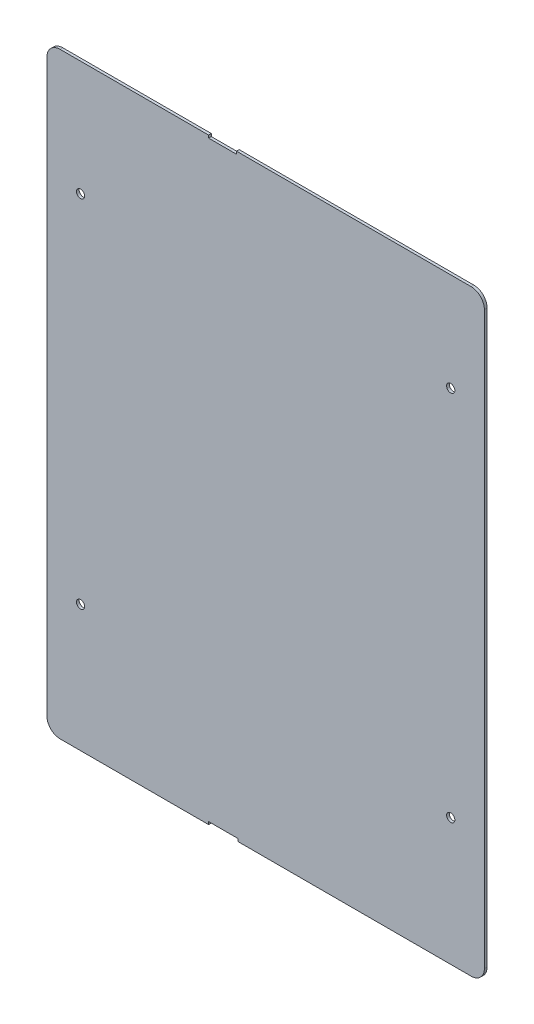
SolidWorks part; units mm, degrees
ref_plane "Front Plane" through (0, 0, 0) normal (0, 0, 1) x (1, 0, 0)
ref_plane "Top Plane" through (0, 0, 0) normal (0, 1, 0) x (1, 0, 0)
ref_plane "Right Plane" through (0, 0, 0) normal (1, 0, 0) x (0, 0, -1)
sketch "Sketch2" plane through (0, 0, 0) normal (0, 0, 1) x (1, 0, 0)
  line L0 (-43, 225.24) -> (-43, 223.24)
  line L1 (-165, 225.24) -> (-43, 225.24)
  line L2 (-165, 225.24) -> (-165, -225.24)
  line L3 (-165, -225.24) -> (-43, -225.24)
  line L4 (165, 225.24) -> (165, -225.24)
  line L5 (-165, 225.24) -> (165, -225.24) construction
  line L6 (-165, -225.24) -> (165, 225.24) construction
  line L7 (-43, 223.24) -> (-22, 223.24)
  line L8 (-22, 223.24) -> (-22, 225.24)
  line L9 (-22, 225.24) -> (165, 225.24)
  line L10 (-21, -225.24) -> (-21, -223.24)
  line L11 (-21, -223.24) -> (-43, -223.24)
  line L12 (-43, -223.24) -> (-43, -225.24)
  line L13 (-21, -225.24) -> (165, -225.24)
  point P0 (0, 0)
  dimension "D1" = 2
  dimension "Length 1" = 330
  dimension "D2" = 122
  dimension "Length 2" = 450.48
  dimension "D3" = 143
  dimension "D4" = 122
  dimension "D5" = 144
  dimension "D6" = 2
extrude "Boss-Extrude1" add sketch "Sketch2" along normal blind 2.032
sketch "Sketch3" [suppressed] plane through (0, 0, 2.032) normal (0, 0, 1) x (1, 0, 0)
  circle A0 centre (-175.117, 128.01) radius 3.1
  circle A1 centre (175.117, 128.01) radius 3.1
  circle A8 centre (-175.1171, -128.01) radius 3.1
  circle A9 centre (175.1169, -128.01) radius 3.1
  dimension "D1" = 6.2
extrude "Cut-Extrude1" [suppressed] cut sketch "Sketch3" against normal through all both and the other way through all
sketch "Sketch4" [suppressed] plane through (0, 0, 0) normal (0, 0, -1) x (-1, 0, 0)
  circle A0 centre (-423.777, 128.01) radius 3.1
  circle A1 centre (423.777, 128.01) radius 3.1
  circle A2 centre (423.777, -128.01) radius 3.1
  circle A3 centre (-423.777, -128.01) radius 3.1
  dimension "D1" = 6.2
extrude "Cut-Extrude2" [suppressed] cut sketch "Sketch4" against normal through all both and the other way through all
sketch "Sketch5" [suppressed] plane through (0, 0, 0) normal (0, 0, -1) x (-1, 0, 0)
  circle A0 centre (-175.117, -437.5) radius 3.1
  circle A1 centre (175.1169, -437.5) radius 3.1
  circle A2 centre (175.1169, 437.5) radius 3.1
  circle A3 centre (-175.117, 437.5) radius 3.1
  dimension "D1" = 6.2
extrude "Cut-Extrude3" [suppressed] cut sketch "Sketch5" against normal through all both and the other way through all
sketch "Sketch6" [suppressed] plane through (0, 0, 0) normal (0, 0, -1) x (-1, 0, 0)
  circle A0 centre (175.9, -175.117) radius 3.1
  circle A1 centre (175.9, 175.117) radius 3.1
  circle A2 centre (-175.9, 175.117) radius 3.1
  circle A3 centre (-175.9, -175.117) radius 3.1
  circle A5 centre (-175.9, 0) radius 3.1
  circle A6 centre (175.9, 0) radius 3.1
  dimension "D1" = 6.2
  dimension "D2" = 6.2
  dimension "D3" = 6.2
fillet "Fillet5" [suppressed] radius 10
extrude "Cut-Extrude4" [suppressed] cut sketch "Sketch6" against normal through all both and the other way through all
sketch "Sketch7" plane through (0, 0, 2.032) normal (0, 0, 1) x (1, 0, 0)
  circle A0 centre (-139.6, -129.6148) radius 3.1
  circle A1 centre (-139.6, 138.5552) radius 3.1
  circle A2 centre (139.6, 151.166) radius 3.1
  circle A3 centre (139.6, -129.36) radius 3.1
  dimension "D1" = 6.2
extrude "Cut-Extrude5" cut sketch "Sketch7" against normal through all both and the other way through all
fillet "Fillet4" radius 10 4 edges at (-165, -225.24, 1.016) (-165, 225.24, 1.016) (165, -225.24, 1.016) (165, 225.24, 1.016)
sketch "Sketch8" [suppressed] plane through (0, 0, 2.032) normal (0, 0, 1) x (1, 0, 0)
  line L0 (-37.3761, -47.01) -> (-37.3761, -22.01) construction
  line L1 (32.5, -51.886) -> (-32.5, -51.886) construction
  line L2 (37.376, -22.01) -> (37.376, -47.01) construction
  line L3 (-32.5, -17.1339) -> (32.5, -17.1339) construction
  line L4 (-37.3761, -47.01) -> (-37.3761, -22.01) construction
  line L5 (32.5, -51.886) -> (-32.5, -51.886) construction
  line L6 (37.376, -22.01) -> (37.376, -47.01) construction
  line L7 (-32.5, -17.1339) -> (32.5, -17.1339) construction
  line L8 (-37.6761, -47.01) -> (-37.6761, -22.01)
  line L9 (32.5, -52.186) -> (-32.5, -52.186)
  line L10 (37.676, -22.01) -> (37.676, -47.01)
  line L11 (-32.5, -16.8339) -> (32.5, -16.8339)
  arc A0 (-37.3761, -47.01) -> (-32.5, -51.886) centre (-32.5, -47.01) ccw construction
  arc A1 (32.5, -51.886) -> (37.376, -47.01) centre (32.5, -47.01) ccw construction
  arc A2 (37.376, -22.01) -> (32.5, -17.1339) centre (32.5, -22.01) ccw construction
  arc A3 (-32.5, -17.1339) -> (-37.3761, -22.01) centre (-32.5, -22.01) ccw construction
  arc A4 (-37.3761, -47.01) -> (-32.5, -51.886) centre (-32.5, -47.01) ccw construction
  arc A5 (32.5, -51.886) -> (37.376, -47.01) centre (32.5, -47.01) ccw construction
  arc A6 (37.376, -22.01) -> (32.5, -17.1339) centre (32.5, -22.01) ccw construction
  arc A7 (-32.5, -17.1339) -> (-37.3761, -22.01) centre (-32.5, -22.01) ccw construction
  arc A8 (-32.5, -16.8339) -> (-37.6761, -22.01) centre (-32.5, -22.01) ccw
  arc A9 (-37.6761, -47.01) -> (-32.5, -52.186) centre (-32.5, -47.01) ccw
  arc A10 (32.5, -52.186) -> (37.676, -47.01) centre (32.5, -47.01) ccw
  arc A11 (37.676, -22.01) -> (32.5, -16.8339) centre (32.5, -22.01) ccw
  dimension "D1" = 0.3
extrude "Cut-Extrude6" [suppressed] cut sketch "Sketch8" against normal through all
sketch "Sketch9" [suppressed] plane through (0, 0, 2.032) normal (0, 0, 1) x (1, 0, 0)
  line L0 (-51.9979, -76.9078) -> (-51.9979, -83.1078) construction
  line L1 (-48.8979, -76.9078) -> (-48.8979, -83.1078)
  line L2 (-55.0979, -76.9078) -> (-55.0979, -83.1078)
  line L3 (51.9978, -76.9078) -> (51.9978, -83.1078) construction
  line L4 (55.0978, -76.9078) -> (55.0978, -83.1078)
  line L5 (48.8978, -76.9078) -> (48.8978, -83.1078)
  circle A0 centre (-51.9979, -1.5121) radius 3.1
  circle A1 centre (51.9978, -1.5121) radius 3.1
  circle A2 centre (-51.9979, -80.0078) radius 3.1 construction
  arc A3 (-48.8979, -76.9078) -> (-55.0979, -76.9078) centre (-51.9979, -76.9078) ccw
  arc A4 (-55.0979, -83.1078) -> (-48.8979, -83.1078) centre (-51.9979, -83.1078) ccw
  circle A5 centre (51.9978, -80.0078) radius 3.1 construction
  arc A6 (55.0978, -76.9078) -> (48.8978, -76.9078) centre (51.9978, -76.9078) ccw
  arc A7 (48.8978, -83.1078) -> (55.0978, -83.1078) centre (51.9978, -83.1078) ccw
  point P11 (-51.9979, -80.0078)
  point P17 (51.9978, -80.0078)
  dimension "D1" = 6.2
extrude "Cut-Extrude7" [suppressed] cut sketch "Sketch9" against normal through all
sketch "Sketch10" [suppressed] plane through (0, 0, 2.032) normal (0, 0, 1) x (1, 0, 0)
  line L0 (90, 90.8143) -> (-90, 90.8143) construction
  line L1 (75.5, 121.0648) -> (-75.5, 121.0648) construction
  line L2 (75.5, 90.8143) -> (-75.5, 90.8143) construction
  line L3 (75.5, 121.0648) -> (-75.5, 121.0648) construction
  line L4 (75.5, 90.5143) -> (-75.5, 90.5143)
  line L5 (75.5, 121.3648) -> (-75.5, 121.3648)
  spline S0 degree 3 poles (7072.6895, 138.2935) (66.7513, 120.7508) (74.0721, 121.0685) (75.5298, 121.0647) (75.5326, 121.0647) (75.6464, 121.0643) (75.8632, 121.0597) (76.1642, 121.0437) (76.381, 121.0257) (76.5878, 121.0048) (76.7942, 120.9803) (77.0603, 120.9413) (77.3248, 120.8952) (77.5598, 120.8477) (77.7949, 120.7947) (77.9818, 120.7481) (78.1109, 120.7132) (78.2822, 120.6658) (78.5457, 120.5872) (78.9382, 120.4526) (79.2301, 120.3392) (79.3912, 120.2721) (79.5867, 120.1894) (79.8287, 120.0797) (80.0659, 119.9615) (80.3074, 119.8374) (80.4668, 119.7503) (80.8016, 119.5566) (81.1538, 119.3396) (81.5223, 119.0841) (81.7178, 118.9395) (81.8836, 118.8158) (82.0678, 118.6719) (82.2476, 118.5231) (82.4279, 118.3716) (82.5907, 118.2288) (82.7493, 118.0824) (82.9322, 117.9119) (83.2327, 117.6176) (83.6639, 117.1527) (83.9602, 116.8013) (84.1153, 116.6069) (84.2773, 116.4024) (84.4141, 116.2207) (84.6783, 115.8519) (84.9333, 115.4777) (85.2917, 114.8964) (85.6175, 114.311) (85.8168, 113.9147) (86.0153, 113.4997) (86.199, 113.0919) (86.3667, 112.6759) (86.5131, 112.2932) (86.6057, 112.0372) (86.6922, 111.7793) (86.7672, 111.5516) (86.8201, 111.3823) (86.9423, 110.9692) (87.0765, 110.4773) (87.247, 109.7286) (87.3625, 109.1005) (87.4598, 108.4609) (87.5282, 107.8937) (87.5661, 107.4468) (87.5939, 107.0493) (87.6148, 106.6536) (87.6234, 106.2582) (87.6251, 106.0243) (87.6252, 105.9711) (87.6249, 105.6521) (87.6131, 105.121) (87.5623, 104.3289) (87.4962, 103.7081) (87.4136, 103.0987) (87.3259, 102.565) (87.2377, 102.1278) (87.1497, 101.7237) (87.0462, 101.2874) (86.9261, 100.8539) (86.8399, 100.5642) (86.8173, 100.4902) (86.7193, 100.1763) (86.5601, 99.7025) (86.2936, 99.0104) (86.0691, 98.4959) (85.9353, 98.2118) (85.8046, 97.939) (85.5968, 97.5281) (85.2615, 96.9315) (84.9154, 96.3749) (84.674, 96.0215) (84.4707, 95.7372) (84.3836, 95.6191) (84.1969, 95.3742) (84.0085, 95.1357) (83.8127, 94.9039) (83.5714, 94.6273) (83.2684, 94.2969) (82.801, 93.8368) (82.325, 93.4136) (81.9762, 93.1336) (81.7857, 92.9898) (81.6442, 92.8839) (81.4108, 92.7157) (81.0521, 92.477) (80.7023, 92.2626) (80.4711, 92.1321) (80.188, 91.9784) (79.8408, 91.802) (79.3125, 91.5689) (78.7817, 91.3682) (78.4002, 91.2473) (78.1974, 91.1898) (78.1177, 91.1676) (77.9122, 91.1121) (77.5556, 91.0277) (77.1709, 90.9552) (76.9362, 90.9195) (76.822, 90.9037) (76.7327, 90.8917) (76.589, 90.8744) (76.4218, 90.8572) (76.2707, 90.8443) (76.119, 90.8335) (75.9751, 90.8254) (75.8173, 90.819) (75.6699, 90.8154) (75.5675, 90.8144) (75.515, 90.8143) (75.5096, 90.8143) (74.7086, 90.8138) (94.8526, 90.9146) (7065.3056, 91.4524) knots -0.003634 -0.003634 -0.003634 -0.003634 0.000024 0.000024 0.000031 0.000031 0.00032 0.000611 0.000881 0.000959 0.001235 0.001516 0.001798 0.002081 0.002271 0.00255 0.002673 0.002673 0.003081 0.003491 0.003902 0.004009 0.004009 0.004534 0.004802 0.004802 0.005346 0.005346 0.00596 0.006584 0.006682 0.006682 0.007198 0.007375 0.007375 0.007897 0.008019 0.008019 0.008644 0.009276 0.009915 0.010016 0.010016 0.010692 0.010692 0.01136 0.012037 0.01273 0.013365 0.013365 0.014106 0.014701 0.014701 0.015325 0.01551 0.01551 0.016038 0.016038 0.016796 0.017562 0.018339 0.018711 0.0195 0.020047 0.020047 0.020686 0.021225 0.021225 0.021384 0.021384 0.022179 0.022975 0.023768 0.024057 0.024824 0.025393 0.025393 0.026061 0.026729 0.026729 0.02696 0.02696 0.027709 0.028454 0.029189 0.029402 0.029402 0.030103 0.030794 0.031468 0.032075 0.032075 0.032512 0.032512 0.032989 0.033412 0.033412 0.03408 0.034748 0.035373 0.035987 0.036085 0.036085 0.036513 0.036938 0.037359 0.037729 0.037729 0.03832 0.038894 0.039463 0.040026 0.040094 0.040094 0.040274 0.04073 0.041182 0.041431 0.041431 0.041522 0.041701 0.041881 0.04206 0.042186 0.042356 0.042495 0.042636 0.042751 0.042751 0.042763 0.042763 0.044724 0.044724 0.044724 0.044724 weights 1 1 1 1 1 1 1 1 1 1 1 1 1 1 1 1 1 1 1 1 1 1 1 1 1 1 1 1 1 1 1 1 1 1 1 1 1 1 1 1 1 1 1 1 1 1 1 1 1 1 1 1 1 1 1 1 1 1 1 1 1 1 1 1 1 1 1 1 1 1 1 1 1 1 1 1 1 1 1 1 1 1 1 1 1 1 1 1 1 1 1 1 1 1 1 1 1 1 1 1 1 1 1 1 1 1 1 1 1 1 1 1 1 1 1 1 1 1 1 1 1 1 1 1 1 1 1 1 1 1 1 1 1 only from (75.5, 121.0648) to (75.5, 90.8143) construction
  spline S1 degree 3 poles (-7069.8966, 91.2945) (-63.0609, 90.9133) (-74.6658, 90.8129) (-75.5178, 90.8143) (-75.5188, 90.8143) (-75.6217, 90.8145) (-75.8102, 90.8179) (-76.0955, 90.831) (-76.3619, 90.851) (-76.5858, 90.8739) (-76.7898, 90.8988) (-76.9915, 90.9272) (-77.2231, 90.9655) (-77.4535, 91.0092) (-77.6838, 91.0585) (-77.9135, 91.1133) (-78.0691, 91.1542) (-78.2957, 91.2169) (-78.5939, 91.3066) (-79.0185, 91.4558) (-79.292, 91.5651) (-79.5791, 91.6863) (-79.8887, 91.8262) (-80.19, 91.98) (-80.431, 92.1099) (-80.5257, 92.1628) (-80.8023, 92.3227) (-81.1645, 92.5459) (-81.531, 92.801) (-81.7204, 92.9414) (-81.86, 93.0454) (-82.1004, 93.2319) (-82.4461, 93.5213) (-82.6659, 93.719) (-82.9234, 93.9587) (-83.2202, 94.2488) (-83.646, 94.7063) (-83.9884, 95.1104) (-84.1878, 95.3632) (-84.3522, 95.5769) (-84.4471, 95.7045) (-84.6398, 95.973) (-84.836, 96.257) (-85.0675, 96.6184) (-85.2256, 96.8798) (-85.2925, 96.9937) (-85.434, 97.2372) (-85.6646, 97.6556) (-85.9851, 98.3049) (-86.2393, 98.8843) (-86.3829, 99.2453) (-86.4494, 99.4187) (-86.55, 99.6841) (-86.6603, 99.9986) (-86.7491, 100.2733) (-86.796, 100.4205) (-86.8377, 100.5557) (-86.8778, 100.6914) (-86.9586, 100.968) (-87.0905, 101.4582) (-87.2577, 102.2029) (-87.3631, 102.7847) (-87.4242, 103.1837) (-87.4447, 103.3291) (-87.4978, 103.7198) (-87.5689, 104.3709) (-87.6172, 105.2208) (-87.6253, 105.7445) (-87.6253, 105.9682) (-87.6252, 105.997) (-87.6239, 106.2925) (-87.6102, 106.8253) (-87.5586, 107.5863) (-87.4824, 108.2948) (-87.3824, 108.9904) (-87.2522, 109.7032) (-87.0975, 110.3876) (-86.9658, 110.8838) (-86.8849, 111.1642) (-86.8565, 111.2593) (-86.8202, 111.38) (-86.7924, 111.4698) (-86.7084, 111.7335) (-86.617, 112.0056) (-86.5018, 112.3221) (-86.4473, 112.4659) (-86.3387, 112.7484) (-86.1745, 113.1489) (-85.9253, 113.6947) (-85.6673, 114.2147) (-85.3669, 114.7671) (-85.0165, 115.3478) (-84.7388, 115.7647) (-84.5819, 115.9866) (-84.4547, 116.1642) (-84.3562, 116.297) (-84.1525, 116.5617) (-83.9899, 116.7652) (-83.8222, 116.9634) (-83.7278, 117.0727) (-83.6931, 117.1124) (-83.512, 117.3171) (-83.2145, 117.6374) (-82.7539, 118.0859) (-82.3108, 118.4763) (-81.9806, 118.7415) (-81.7867, 118.8888) (-81.7261, 118.9339) (-81.5923, 119.0328) (-81.36, 119.1984) (-81.006, 119.4314) (-80.7579, 119.5818) (-80.6329, 119.6543) (-80.5302, 119.7137) (-80.4331, 119.768) (-80.1632, 119.9135) (-79.8189, 120.0873) (-79.2869, 120.3208) (-78.7504, 120.5219) (-78.374, 120.6396) (-78.1216, 120.7105) (-77.9102, 120.7674) (-77.5659, 120.8488) (-77.1858, 120.9214) (-76.9471, 120.958) (-76.8184, 120.9759) (-76.7272, 120.988) (-76.582, 121.0054) (-76.4149, 121.0225) (-76.2649, 121.0352) (-76.1143, 121.0458) (-75.972, 121.0538) (-75.8151, 121.0601) (-75.6689, 121.0637) (-75.5671, 121.0646) (-75.515, 121.0648) (-75.5096, 121.0648) (-74.7124, 121.0652) (-94.9263, 120.9652) (-7066.4179, 120.4324) knots -0.001957 -0.001957 -0.001957 -0.001957 0.000013 0.000013 0.000016 0.000016 0.000262 0.000488 0.000778 0.001021 0.001162 0.001413 0.001666 0.001921 0.002175 0.002427 0.002667 0.002667 0.00313 0.003594 0.004001 0.004001 0.004517 0.00501 0.00501 0.005334 0.005334 0.005966 0.006608 0.006668 0.006668 0.007126 0.007571 0.008002 0.008002 0.008616 0.009237 0.009867 0.010196 0.010196 0.010669 0.010669 0.011178 0.011692 0.011939 0.012084 0.012084 0.012777 0.013509 0.014247 0.014667 0.014667 0.0148 0.015513 0.015656 0.015656 0.015971 0.016076 0.016076 0.016826 0.017586 0.018355 0.018595 0.018795 0.018795 0.019775 0.020751 0.02133 0.02133 0.021415 0.021415 0.022207 0.023001 0.023696 0.024344 0.025112 0.025872 0.026446 0.026646 0.026742 0.026742 0.027021 0.027021 0.027563 0.027871 0.02802 0.02802 0.028771 0.029311 0.029815 0.03051 0.031195 0.031844 0.032003 0.032003 0.032493 0.032493 0.032991 0.033263 0.033263 0.033421 0.033421 0.034077 0.034725 0.035343 0.035843 0.035988 0.036067 0.036067 0.036482 0.036912 0.037319 0.037341 0.037341 0.037673 0.037673 0.038257 0.038828 0.039418 0.039978 0.040009 0.040201 0.04063 0.041056 0.041342 0.041342 0.04144 0.041618 0.041798 0.041977 0.042099 0.042269 0.042405 0.042545 0.04266 0.04266 0.042671 0.042671 0.044622 0.044622 0.044622 0.044622 weights 1 1 1 1 1 1 1 1 1 1 1 1 1 1 1 1 1 1 1 1 1 1 1 1 1 1 1 1 1 1 1 1 1 1 1 1 1 1 1 1 1 1 1 1 1 1 1 1 1 1 1 1 1 1 1 1 1 1 1 1 1 1 1 1 1 1 1 1 1 1 1 1 1 1 1 1 1 1 1 1 1 1 1 1 1 1 1 1 1 1 1 1 1 1 1 1 1 1 1 1 1 1 1 1 1 1 1 1 1 1 1 1 1 1 1 1 1 1 1 1 1 1 1 1 1 1 1 1 1 1 1 1 1 1 1 1 1 1 1 1 only from (-75.5, 90.8143) to (-75.5, 121.0648) construction
  spline S2 degree 3 poles (75.5, 121.0648) (75.5079, 121.0648) (75.5205, 121.0647) (75.5326, 121.0647) (75.6464, 121.0643) (75.8632, 121.0597) (76.1642, 121.0437) (76.381, 121.0257) (76.5878, 121.0048) (76.7942, 120.9803) (77.0603, 120.9413) (77.3248, 120.8952) (77.5598, 120.8477) (77.7949, 120.7947) (77.9818, 120.7481) (78.1109, 120.7132) (78.2822, 120.6658) (78.5457, 120.5872) (78.9382, 120.4526) (79.2301, 120.3392) (79.3912, 120.2721) (79.5867, 120.1894) (79.8287, 120.0797) (80.0659, 119.9615) (80.3074, 119.8374) (80.4668, 119.7503) (80.8016, 119.5566) (81.1538, 119.3396) (81.5223, 119.0841) (81.7178, 118.9395) (81.8836, 118.8158) (82.0678, 118.6719) (82.2476, 118.5231) (82.4279, 118.3716) (82.5907, 118.2288) (82.7493, 118.0824) (82.9322, 117.9119) (83.2327, 117.6176) (83.6639, 117.1527) (83.9602, 116.8013) (84.1153, 116.6069) (84.2773, 116.4024) (84.4141, 116.2207) (84.6783, 115.8519) (84.9333, 115.4777) (85.2917, 114.8964) (85.6175, 114.311) (85.8168, 113.9147) (86.0153, 113.4997) (86.199, 113.0919) (86.3667, 112.6759) (86.5131, 112.2932) (86.6057, 112.0372) (86.6922, 111.7793) (86.7672, 111.5516) (86.8201, 111.3823) (86.9423, 110.9692) (87.0765, 110.4773) (87.247, 109.7286) (87.3625, 109.1005) (87.4598, 108.4609) (87.5282, 107.8937) (87.5661, 107.4468) (87.5939, 107.0493) (87.6148, 106.6536) (87.6234, 106.2582) (87.6251, 106.0243) (87.6252, 105.9711) (87.6249, 105.6521) (87.6131, 105.121) (87.5623, 104.3289) (87.4962, 103.7081) (87.4136, 103.0987) (87.3259, 102.565) (87.2377, 102.1278) (87.1497, 101.7237) (87.0462, 101.2874) (86.9261, 100.8539) (86.8399, 100.5642) (86.8173, 100.4902) (86.7193, 100.1763) (86.5601, 99.7025) (86.2936, 99.0104) (86.0691, 98.4959) (85.9353, 98.2118) (85.8046, 97.939) (85.5968, 97.5281) (85.2615, 96.9315) (84.9154, 96.3749) (84.674, 96.0215) (84.4707, 95.7372) (84.3836, 95.6191) (84.1969, 95.3742) (84.0085, 95.1357) (83.8127, 94.9039) (83.5714, 94.6273) (83.2684, 94.2969) (82.801, 93.8368) (82.325, 93.4136) (81.9762, 93.1336) (81.7857, 92.9898) (81.6442, 92.8839) (81.4108, 92.7157) (81.0521, 92.477) (80.7023, 92.2626) (80.4711, 92.1321) (80.188, 91.9784) (79.8408, 91.802) (79.3125, 91.5689) (78.7817, 91.3682) (78.4002, 91.2473) (78.1974, 91.1898) (78.1177, 91.1676) (77.9122, 91.1121) (77.5556, 91.0277) (77.1709, 90.9552) (76.9362, 90.9195) (76.822, 90.9037) (76.7327, 90.8917) (76.589, 90.8744) (76.4218, 90.8572) (76.2707, 90.8443) (76.119, 90.8335) (75.9751, 90.8254) (75.8173, 90.819) (75.6699, 90.8154) (75.5675, 90.8144) (75.515, 90.8143) (75.5076, 90.8143) (75.5015, 90.8143) (75.5, 90.8143) knots 0 0 0 0 0.000024 0.000031 0.000031 0.00032 0.000611 0.000881 0.000959 0.001235 0.001516 0.001798 0.002081 0.002271 0.00255 0.002673 0.002673 0.003081 0.003491 0.003902 0.004009 0.004009 0.004534 0.004802 0.004802 0.005346 0.005346 0.00596 0.006584 0.006682 0.006682 0.007198 0.007375 0.007375 0.007897 0.008019 0.008019 0.008644 0.009276 0.009915 0.010016 0.010016 0.010692 0.010692 0.01136 0.012037 0.01273 0.013365 0.013365 0.014106 0.014701 0.014701 0.015325 0.01551 0.01551 0.016038 0.016038 0.016796 0.017562 0.018339 0.018711 0.0195 0.020047 0.020047 0.020686 0.021225 0.021225 0.021384 0.021384 0.022179 0.022975 0.023768 0.024057 0.024824 0.025393 0.025393 0.026061 0.026729 0.026729 0.02696 0.02696 0.027709 0.028454 0.029189 0.029402 0.029402 0.030103 0.030794 0.031468 0.032075 0.032075 0.032512 0.032512 0.032989 0.033412 0.033412 0.03408 0.034748 0.035373 0.035987 0.036085 0.036085 0.036513 0.036938 0.037359 0.037729 0.037729 0.03832 0.038894 0.039463 0.040026 0.040094 0.040094 0.040274 0.04073 0.041182 0.041431 0.041431 0.041522 0.041701 0.041881 0.04206 0.042186 0.042356 0.042495 0.042636 0.042751 0.042751 0.042763 0.042767 0.042767 0.042767 0.042767 weights 1 1 1 1 1 1 1 1 1 1 1 1 1 1 1 1 1 1 1 1 1 1 1 1 1 1 1 1 1 1 1 1 1 1 1 1 1 1 1 1 1 1 1 1 1 1 1 1 1 1 1 1 1 1 1 1 1 1 1 1 1 1 1 1 1 1 1 1 1 1 1 1 1 1 1 1 1 1 1 1 1 1 1 1 1 1 1 1 1 1 1 1 1 1 1 1 1 1 1 1 1 1 1 1 1 1 1 1 1 1 1 1 1 1 1 1 1 1 1 1 1 1 1 1 1 1 1 1 1 1 1 construction
  spline S3 degree 3 poles (-75.5, 90.8143) (-75.5046, 90.8143) (-75.512, 90.8143) (-75.5188, 90.8143) (-75.6217, 90.8145) (-75.8102, 90.8179) (-76.0955, 90.831) (-76.3619, 90.851) (-76.5858, 90.8739) (-76.7898, 90.8988) (-76.9915, 90.9272) (-77.2231, 90.9655) (-77.4535, 91.0092) (-77.6838, 91.0585) (-77.9135, 91.1133) (-78.0691, 91.1542) (-78.2957, 91.2169) (-78.5939, 91.3066) (-79.0185, 91.4558) (-79.292, 91.5651) (-79.5791, 91.6863) (-79.8887, 91.8262) (-80.19, 91.98) (-80.431, 92.1099) (-80.5257, 92.1628) (-80.8023, 92.3227) (-81.1645, 92.5459) (-81.531, 92.801) (-81.7204, 92.9414) (-81.86, 93.0454) (-82.1004, 93.2319) (-82.4461, 93.5213) (-82.6659, 93.719) (-82.9234, 93.9587) (-83.2202, 94.2488) (-83.646, 94.7063) (-83.9884, 95.1104) (-84.1878, 95.3632) (-84.3522, 95.5769) (-84.4471, 95.7045) (-84.6398, 95.973) (-84.836, 96.257) (-85.0675, 96.6184) (-85.2256, 96.8798) (-85.2925, 96.9937) (-85.434, 97.2372) (-85.6646, 97.6556) (-85.9851, 98.3049) (-86.2393, 98.8843) (-86.3829, 99.2453) (-86.4494, 99.4187) (-86.55, 99.6841) (-86.6603, 99.9986) (-86.7491, 100.2733) (-86.796, 100.4205) (-86.8377, 100.5557) (-86.8778, 100.6914) (-86.9586, 100.968) (-87.0905, 101.4582) (-87.2577, 102.2029) (-87.3631, 102.7847) (-87.4242, 103.1837) (-87.4447, 103.3291) (-87.4978, 103.7198) (-87.5689, 104.3709) (-87.6172, 105.2208) (-87.6253, 105.7445) (-87.6253, 105.9682) (-87.6252, 105.997) (-87.6239, 106.2925) (-87.6102, 106.8253) (-87.5586, 107.5863) (-87.4824, 108.2948) (-87.3824, 108.9904) (-87.2522, 109.7032) (-87.0975, 110.3876) (-86.9658, 110.8838) (-86.8849, 111.1642) (-86.8565, 111.2593) (-86.8202, 111.38) (-86.7924, 111.4698) (-86.7084, 111.7335) (-86.617, 112.0056) (-86.5018, 112.3221) (-86.4473, 112.4659) (-86.3387, 112.7484) (-86.1745, 113.1489) (-85.9253, 113.6947) (-85.6673, 114.2147) (-85.3669, 114.7671) (-85.0165, 115.3478) (-84.7388, 115.7647) (-84.5819, 115.9866) (-84.4547, 116.1642) (-84.3562, 116.297) (-84.1525, 116.5617) (-83.9899, 116.7652) (-83.8222, 116.9634) (-83.7278, 117.0727) (-83.6931, 117.1124) (-83.512, 117.3171) (-83.2145, 117.6374) (-82.7539, 118.0859) (-82.3108, 118.4763) (-81.9806, 118.7415) (-81.7867, 118.8888) (-81.7261, 118.9339) (-81.5923, 119.0328) (-81.36, 119.1984) (-81.006, 119.4314) (-80.7579, 119.5818) (-80.6329, 119.6543) (-80.5302, 119.7137) (-80.4331, 119.768) (-80.1632, 119.9135) (-79.8189, 120.0873) (-79.2869, 120.3208) (-78.7504, 120.5219) (-78.374, 120.6396) (-78.1216, 120.7105) (-77.9102, 120.7674) (-77.5659, 120.8488) (-77.1858, 120.9214) (-76.9471, 120.958) (-76.8184, 120.9759) (-76.7272, 120.988) (-76.582, 121.0054) (-76.4149, 121.0225) (-76.2649, 121.0352) (-76.1143, 121.0458) (-75.972, 121.0538) (-75.8151, 121.0601) (-75.6689, 121.0637) (-75.5671, 121.0646) (-75.515, 121.0648) (-75.5076, 121.0648) (-75.5015, 121.0648) (-75.5, 121.0648) knots 0 0 0 0 0.000013 0.000016 0.000016 0.000262 0.000488 0.000778 0.001021 0.001162 0.001413 0.001666 0.001921 0.002175 0.002427 0.002667 0.002667 0.00313 0.003594 0.004001 0.004001 0.004517 0.00501 0.00501 0.005334 0.005334 0.005966 0.006608 0.006668 0.006668 0.007126 0.007571 0.008002 0.008002 0.008616 0.009237 0.009867 0.010196 0.010196 0.010669 0.010669 0.011178 0.011692 0.011939 0.012084 0.012084 0.012777 0.013509 0.014247 0.014667 0.014667 0.0148 0.015513 0.015656 0.015656 0.015971 0.016076 0.016076 0.016826 0.017586 0.018355 0.018595 0.018795 0.018795 0.019775 0.020751 0.02133 0.02133 0.021415 0.021415 0.022207 0.023001 0.023696 0.024344 0.025112 0.025872 0.026446 0.026646 0.026742 0.026742 0.027021 0.027021 0.027563 0.027871 0.02802 0.02802 0.028771 0.029311 0.029815 0.03051 0.031195 0.031844 0.032003 0.032003 0.032493 0.032493 0.032991 0.033263 0.033263 0.033421 0.033421 0.034077 0.034725 0.035343 0.035843 0.035988 0.036067 0.036067 0.036482 0.036912 0.037319 0.037341 0.037341 0.037673 0.037673 0.038257 0.038828 0.039418 0.039978 0.040009 0.040201 0.04063 0.041056 0.041342 0.041342 0.04144 0.041618 0.041798 0.041977 0.042099 0.042269 0.042405 0.042545 0.04266 0.04266 0.042671 0.042676 0.042676 0.042676 0.042676 weights 1 1 1 1 1 1 1 1 1 1 1 1 1 1 1 1 1 1 1 1 1 1 1 1 1 1 1 1 1 1 1 1 1 1 1 1 1 1 1 1 1 1 1 1 1 1 1 1 1 1 1 1 1 1 1 1 1 1 1 1 1 1 1 1 1 1 1 1 1 1 1 1 1 1 1 1 1 1 1 1 1 1 1 1 1 1 1 1 1 1 1 1 1 1 1 1 1 1 1 1 1 1 1 1 1 1 1 1 1 1 1 1 1 1 1 1 1 1 1 1 1 1 1 1 1 1 1 1 1 1 1 1 1 1 1 1 1 1 construction
  spline S4 degree 1 poles (-75.5, 90.5143) (-75.5, 121.3648) knots 0 0 1 1 construction
  spline S5 degree 1 poles (75.5, 121.3648) (75.5, 90.5143) knots 0 0 1 1 construction
  spline S6 degree 3 poles (-75.5, 90.5143) (-75.6364, 90.5143) (-75.9178, 90.5203) (-76.4106, 90.5505) (-76.9682, 90.6146) (-77.583, 90.724) (-78.4367, 90.929) (-79.5539, 91.3171) (-81.1922, 92.1383) (-83.046, 93.5297) (-85.4559, 96.3039) (-87.4217, 100.5003) (-88.1781, 105.9528) (-87.4175, 111.3767) (-85.4702, 115.556) (-83.3502, 117.9986) (-81.9517, 119.1724) (-80.7872, 119.944) (-79.56, 120.5575) (-78.4813, 120.9369) (-77.5849, 121.1564) (-77.0009, 121.2574) (-76.5584, 121.3109) (-76.2401, 121.3392) (-75.9079, 121.3589) (-75.6314, 121.3648) (-75.5, 121.3648) knots 0 0 0 0 0.000333 0.000667 0.001334 0.002 0.002667 0.004001 0.005334 0.008002 0.010669 0.016003 0.021338 0.026672 0.032007 0.034674 0.036008 0.037341 0.038675 0.040009 0.040675 0.041342 0.041676 0.042009 0.042342 0.042676 0.042676 0.042676 0.042676
  spline S7 degree 3 poles (75.5, 121.3648) (75.7505, 121.3647) (76.2699, 121.3441) (76.935, 121.2693) (77.5771, 121.1569) (78.4459, 120.9475) (79.5593, 120.5593) (81.1959, 119.7385) (83.0542, 118.3419) (85.4627, 115.5649) (87.0341, 112.198) (87.7984, 108.6558) (87.9891, 105.9096) (87.7964, 103.2116) (87.0182, 99.6349) (85.4812, 96.3435) (83.3563, 93.8861) (81.9584, 92.712) (80.7938, 91.9388) (79.5626, 91.3225) (78.483, 90.9427) (77.5871, 90.7231) (77.0029, 90.622) (76.5596, 90.5682) (76.2408, 90.5399) (75.9082, 90.5202) (75.6315, 90.5143) (75.5, 90.5143) knots 0 0 0 0 0.000668 0.001336 0.002005 0.002673 0.004009 0.005346 0.008019 0.010692 0.016038 0.018711 0.021384 0.024056 0.026729 0.032075 0.034748 0.036085 0.037421 0.038758 0.040094 0.040762 0.041431 0.041765 0.042099 0.042433 0.042767 0.042767 0.042767 0.042767
  dimension "D1" = 0.3
extrude "Cut-Extrude8" [suppressed] cut sketch "Sketch10" against normal through all
sketch "Sketch11" [suppressed] plane through (0, 0, 2.032) normal (0, 0, 1) x (1, 0, 0)
